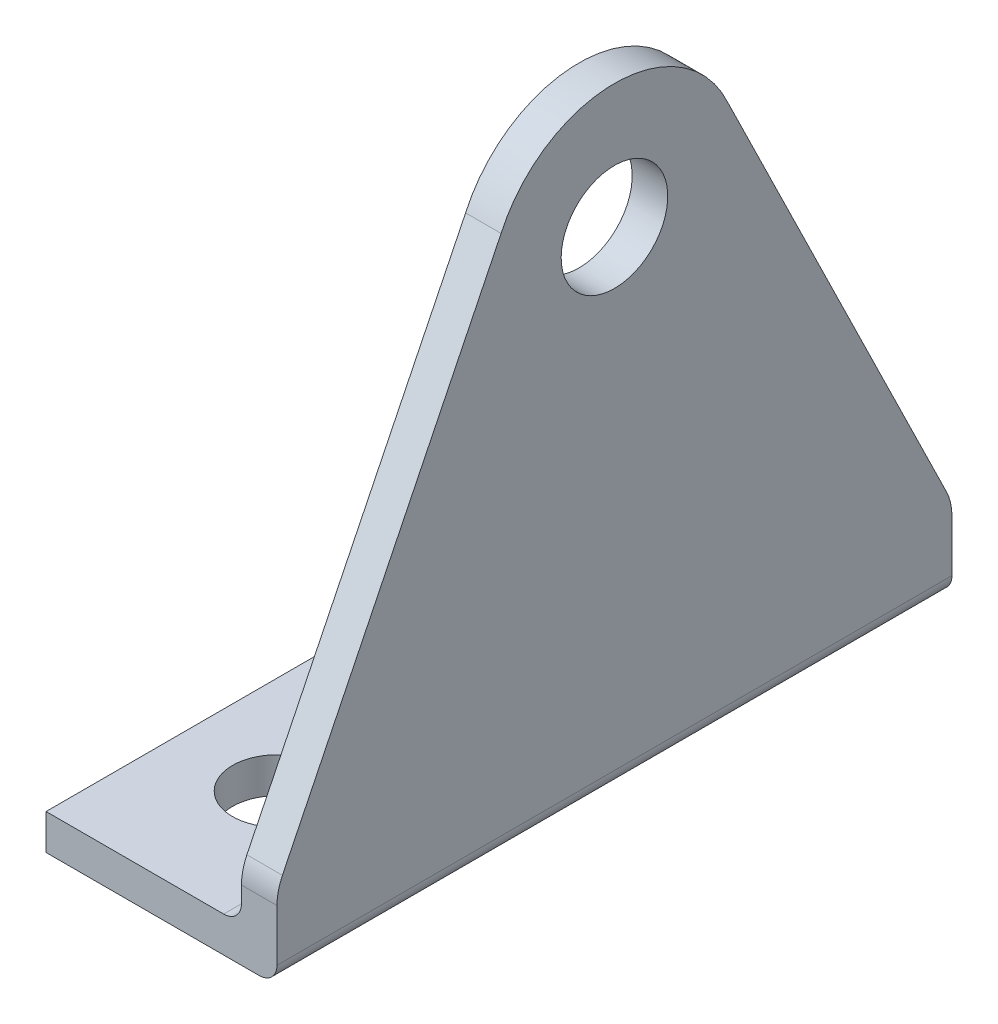
SolidWorks part; units mm, degrees
ref_plane "前视基准面" through (0, 0, 0) normal (0, 0, 1) x (1, 0, 0)
ref_plane "上视基准面" through (0, 0, 0) normal (0, 1, 0) x (1, 0, 0)
ref_plane "右视基准面" through (0, 0, 0) normal (1, 0, 0) x (0, 0, -1)
other "Configuration Table"
sketch "草图1" plane through (0, 0, 0) normal (0, 0, 1) x (1, 0, 0)
  line L0 (0, 1) -> (0, 34.5)
  line L1 (-1, 0) -> (-13, 0)
  line L2 (-3, 2) -> (-13, 2)
  line L3 (-2, 3) -> (-2, 34.5)
  line L4 (-2, 2) -> (-13, 2) construction
  line L5 (-2, 2) -> (-2, 34.5) construction
  line L6 (-13, 2) -> (-13, 0)
  line L7 (-2, 34.5) -> (0, 34.5)
  arc A0 (0, 1) -> (-1, 0) centre (-1, 1) cw
  arc A2 (-3, 2) -> (-2, 3) centre (-3, 3) ccw
  arc A3 (-2, 2) -> (-2, 2) centre (-2, 2) cw construction
  point P6 (0, 0)
  dimension "D3" = 1
  dimension "D5" = 1
  dimension "D1" = 34.5
  dimension "D2" = 13
  dimension "D4" = 2
extrude "凸台-拉伸1" add sketch "草图1" along normal blind 38
sketch "草图2" plane through (0, 2, 0) normal (0, 1, 0) x (1, 0, 0)
  line L0 (-13, -19) -> (8.1779, -19) construction
  line L1 (-13, -38) -> (-13, 0) construction
  line L2 (-3, 0) -> (-13, 0) construction
  circle A0 centre (-7.5, -7.5) radius 2.5
  circle A1 centre (-7.5, -30.5) radius 2.5
  dimension "D1" = 5
  dimension "D3" = 5.5
  dimension "D2" = 7.5
extrude "切除-拉伸1" cut sketch "草图2" against normal through all
sketch "草图3" plane through (-2, 0, 0) normal (-1, 0, 0) x (0, 0, 1)
  line L0 (19, 34.5) -> (19, -2.1787) construction
  line L1 (38, 34.5) -> (0, 34.5) construction
  circle A0 centre (19, 27.5) radius 3
  dimension "D1" = 6
  dimension "D2" = 7
extrude "切除-拉伸2" cut sketch "草图3" against normal through all
sketch "草图4" plane through (-2, 0, 0) normal (-1, 0, 0) x (0, 0, 1)
  line L0 (19, 27.5) -> (19, 3) construction
  line L1 (38, 34.5) -> (0, 34.5) construction
  line L2 (0, 3.9169) -> (0, 34.5)
  line L12 (0, 34.5) -> (38, 34.5)
  line L13 (0, 34.5) -> (0, 3) construction
  line L14 (0.3058, 5.2364) -> (12.6184, 30.3767)
  line L15 (38, 3.9169) -> (38, 34.5)
  line L16 (37.6942, 5.2364) -> (25.3816, 30.3767)
  circle A0 centre (19, 27.5) radius 3 construction
  circle A1 centre (19, 27.5) radius 3
  arc A2 (12.6184, 30.3767) -> (25.3816, 30.3767) centre (19, 27.5) cw
  arc A3 (0, 3.9169) -> (0.3058, 5.2364) centre (3, 3.9169) cw
  arc A4 (38, 3.9169) -> (37.6942, 5.2364) centre (35, 3.9169) ccw
  point P20 (0, 4.6121)
  point P23 (19, 34.5)
  line M14 (0, 34.5) -> (0, 3)
  line M16 (38, 3) -> (38, 34.5)
  line M17 (38, 34.5) -> (0, 34.5)
  dimension "D1" = 3
  dimension "D2" = 25.1402
  dimension "D3" = 12.6184
extrude "切除-拉伸3" cut sketch "草图4" against normal through all contours A3 L14 A2 L12 M14 | A4 A2 L16 M16 M17
